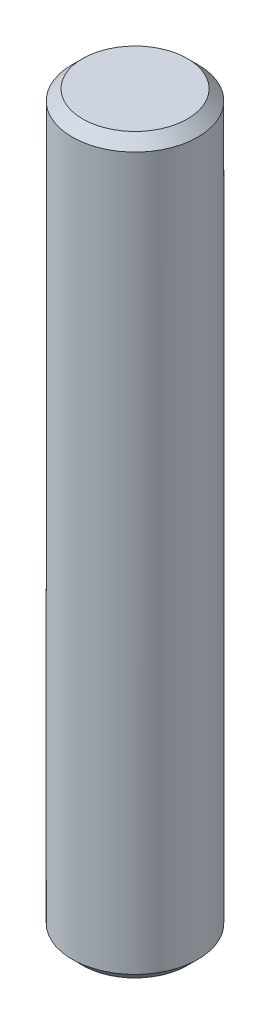
SolidWorks part; units mm, degrees
material "Alloy Steel (SS)"
ref_plane "Front Plane" through (0, 0, 0) normal (0, 0, 1) x (1, 0, 0)
ref_plane "Top Plane" through (0, 0, 0) normal (0, 1, 0) x (1, 0, 0)
ref_plane "Right Plane" through (0, 0, 0) normal (1, 0, 0) x (0, 0, -1)
sketch "Sketch1" plane through (0, 0, 0) normal (0, 0, 1) x (1, 0, 0)
  line L1 (0, 0) -> (6, 0)
  line L2 (0, 0) -> (0, 70)
  line L3 (0, 70) -> (6, 70)
  line L4 (6, 0) -> (6, 70)
  dimension "D1" = 6
  dimension "D2" = 70
revolve "Revolve1" add sketch "Sketch1" angle 360 about L2
cosmetic thread "Cosmetic Thread1"
cosmetic thread "Cosmetic Thread2"
chamfer "Chamfer1" distance 1 angle 45 2 edges at (0, 0, -6) (0, 70, -6)
